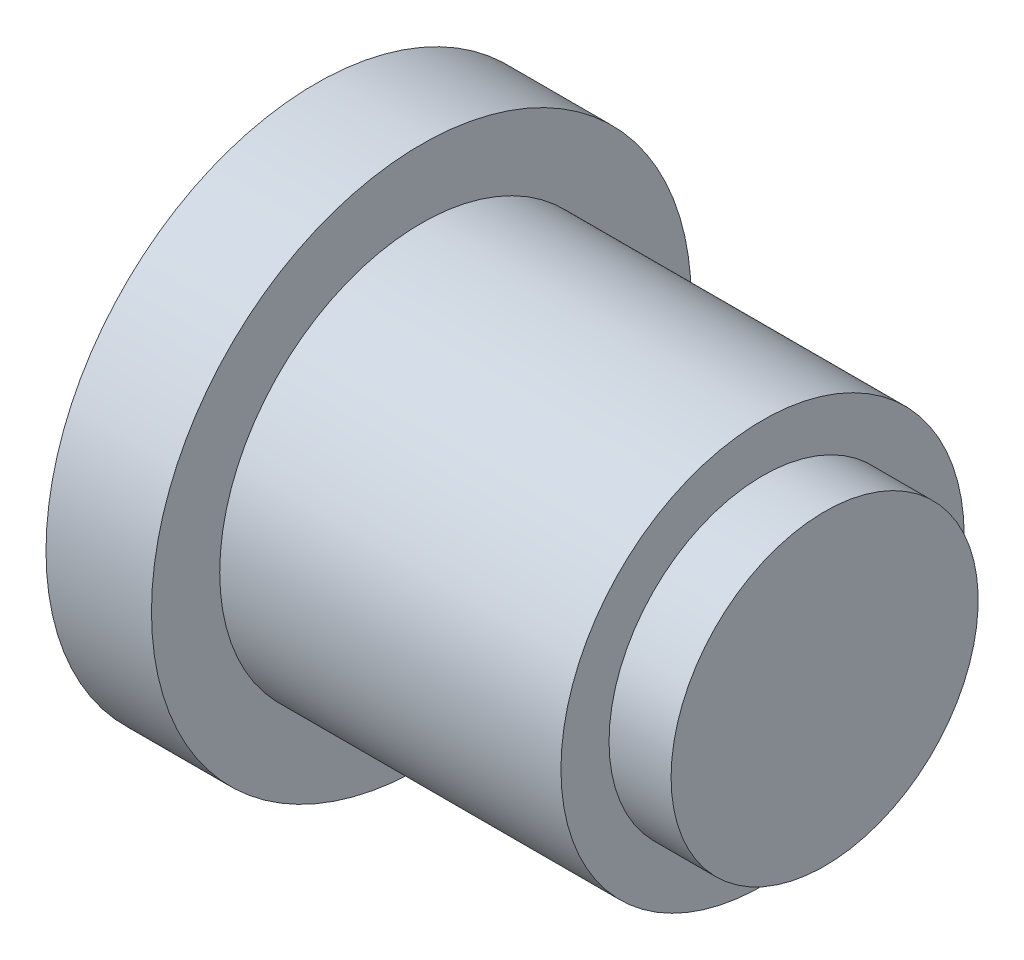
SolidWorks part; units mm, degrees
ref_plane "正面" through (0, 0, 0) normal (0, 0, 1) x (1, 0, 0)
ref_plane "平面" through (0, 0, 0) normal (0, 1, 0) x (1, 0, 0)
ref_plane "右側面" through (0, 0, 0) normal (1, 0, 0) x (0, 0, -1)
sketch "ｽｹｯﾁ1" plane through (0, 0, 0) normal (0, 0, 1) x (1, 0, 0)
  line L0 (0, 0) -> (0, 87)
  line L1 (0, 87) -> (34, 87)
  line L2 (34, 87) -> (34, 65)
  line L3 (34, 65) -> (144, 65)
  line L4 (144, 65) -> (144, 49.5)
  line L5 (144, 49.5) -> (164, 49.5)
  line L6 (164, 49.5) -> (164, 0)
  line L7 (164, 0) -> (0, 0)
  line L8 (0, 0) -> (164, 0) construction
revolve "回転1" add sketch "ｽｹｯﾁ1" angle 360 about L8
